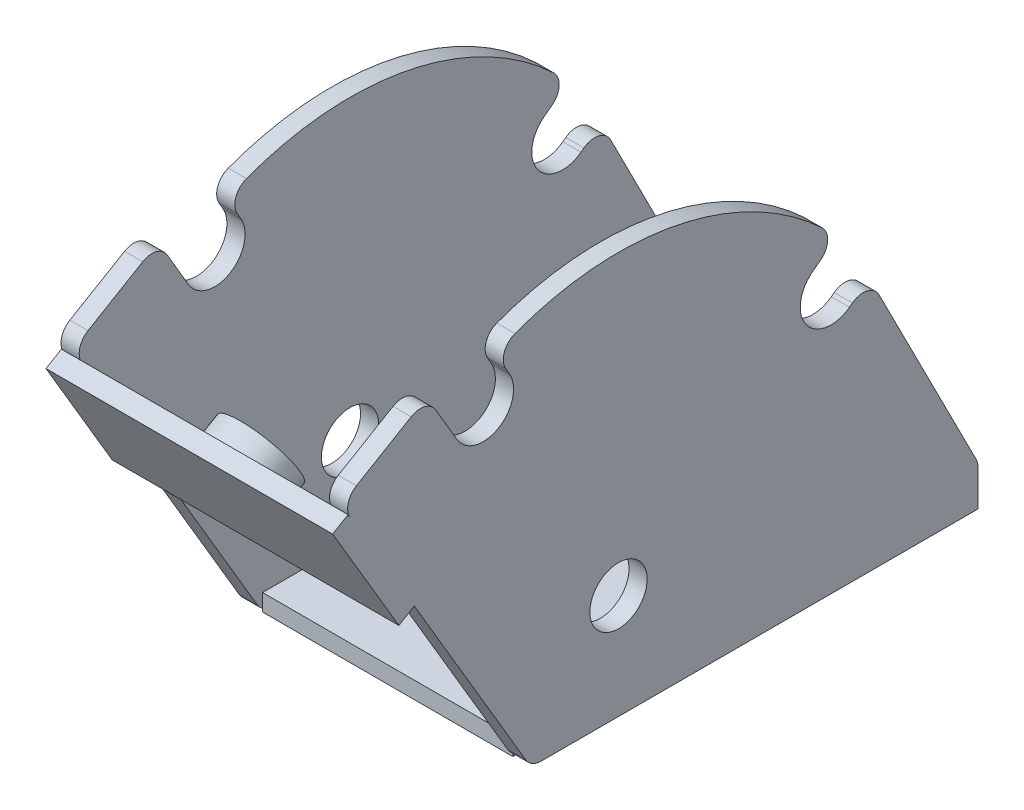
SolidWorks part; units mm, degrees
ref_plane "Front Plane" through (0, 0, 0) normal (0, 0, 1) x (1, 0, 0)
ref_plane "Top Plane" through (0, 0, 0) normal (0, 1, 0) x (1, 0, 0)
ref_plane "Right Plane" through (0, 0, 0) normal (1, 0, 0) x (0, 0, -1)
sketch "Sketch1" plane through (0, 0, 0) normal (0, 1, 0) x (1, 0, 0)
  line L0 (0, -1000) -> (0, 49000) construction
  line L1 (-17.78, -31.75) -> (17.78, -31.75)
  line L2 (-17.78, -31.75) -> (-17.78, 31.75)
  line L3 (-17.78, 31.75) -> (17.78, 31.75)
  line L4 (17.78, -31.75) -> (17.78, 31.75)
  line L5 (-17.78, -31.75) -> (17.78, 31.75) construction
  line L6 (-17.78, 31.75) -> (17.78, -31.75) construction
  circle A0 centre (-11.0109, 18.288) radius 3.0734
  circle A1 centre (-11.0109, -22.225) radius 3.0734
  circle A2 centre (11.0109, -22.225) radius 3.0734
  circle A3 centre (11.0109, 18.288) radius 3.0734
  point P0 (0, 0)
  dimension "D3" = 6.1468
  dimension "D1" = 35.56
  dimension "D2" = 63.5
  dimension "D4" = 9.525
  dimension "D5" = 6.7691
  dimension "D6" = 13.462
extrude "Boss-Extrude1" add sketch "Sketch1" along normal blind 2.4003
sketch "Sketch2" plane through (17.78, 0, 0) normal (1, 0, 0) x (0, 0, -1)
  line L0 (31.75, 0) -> (31.75, 5.1191)
  line L1 (31.75, 0) -> (-30.2995, 0)
  line L2 (-32.4871, 1.2492) -> (-57.4371, 43.5324)
  line L3 (-35.3361, 50.8042) -> (-34.8166, 49.9161)
  line L4 (31.4742, 6.2702) -> (17.6936, 33.377)
  line L5 (-45.2777, 50.696) -> (-42.271, 45.5558)
  line L6 (-56.5403, 47.0108) -> (-48.761, 51.6011)
  line L7 (-42.271, 45.5558) -> (-34.8166, 49.9161) construction
  line L8 (9.3783, 41.7831) -> (8.2564, 40.944)
  line L9 (13.908, 34.2599) -> (13.4898, 33.9471)
  line L10 (8.2564, 40.944) -> (13.4898, 33.9471) construction
  line L11 (-38.5438, 47.7359) -> (-19.3166, 14.8653) construction
  line L12 (-19.3166, 14.8653) -> (10.8731, 37.4455) construction
  arc A0 (-34.0281, 54.4677) -> (9.5952, 45.6691) centre (-19.3166, 14.8653) cw
  circle A1 centre (-19.3166, 14.8653) radius 4.0704
  arc A2 (-42.271, 45.5558) -> (-34.8166, 49.9161) centre (-38.5438, 47.7359) ccw
  arc A3 (8.2564, 40.944) -> (13.4898, 33.9471) centre (10.8731, 37.4455) ccw
  arc A4 (-30.2995, 0) -> (-32.4871, 1.2492) centre (-30.2995, 2.54) cw
  arc A5 (31.75, 5.1191) -> (31.4742, 6.2702) centre (29.21, 5.1191) ccw
  arc A6 (17.6936, 33.377) -> (13.908, 34.2599) centre (15.4294, 32.2259) ccw
  arc A7 (9.5952, 45.6691) -> (9.3783, 41.7831) centre (7.857, 43.8171) cw
  arc A8 (-35.3361, 50.8042) -> (-34.0281, 54.4677) centre (-33.1436, 52.0867) cw
  arc A9 (-45.2777, 50.696) -> (-48.761, 51.6011) centre (-47.4701, 49.4136) ccw
  arc A10 (-57.4371, 43.5324) -> (-56.5403, 47.0108) centre (-55.2495, 44.8232) cw
  point P20 (-31.75, 0)
  point P23 (31.75, 5.7277)
  point P26 (16.3255, 36.068)
  point P33 (-46.565, 52.8969)
  point P36 (-58.7279, 45.72)
  dimension "D2" = 8.1407
  dimension "D12" = 42.2465
  dimension "D15" = 2.54
  dimension "D1" = 14.8654
  dimension "D3" = 18.2626
  dimension "D4" = 53.086
  dimension "D5" = 45.72
  dimension "D6" = 14.1224
  dimension "D7" = 8.636
  dimension "D8" = 38.0809
  dimension "D9" = 34.036
  dimension "D10" = 5.7277
  dimension "D11" = 36.068
  dimension "D13" = 8.7376
  dimension "D14" = 37.6999
extrude "Boss-Extrude2" add sketch "Sketch2" along normal blind 2.5781
ref_plane "Plane1" through (0, 0, 0) normal (-1, 0, 0) x (0, 0, 1)
mirror "Mirror1" about plane through (0, 0, 0) normal (-1, 0, 0) of "Boss-Extrude2"
sketch "Sketch3" plane through (0, -13.8962, 23.5503) normal (0, -0.5082, 0.8612) x (1, 0, 0)
  line L0 (-20.3581, 66.6811) -> (-20.3581, 17.5855) construction
  line L1 (-20.3581, 48.7585) -> (20.3581, 48.7585)
  line L2 (-20.3581, 48.7585) -> (-20.3581, 67.2751)
  line L3 (-20.3581, 67.2751) -> (20.3581, 67.2751)
  line L4 (20.3581, 48.7585) -> (20.3581, 67.2751)
  line L5 (20.3581, 66.6811) -> (20.3581, 17.5855) construction
  line L6 (-17.78, 18.2023) -> (17.78, 18.2023) construction
  dimension "D1" = 18.5166
  dimension "D2" = 30.5562
extrude "Boss-Extrude3" add sketch "Sketch3" along normal blind 2.54
sketch "Sketch4" plane through (0, -13.8962, 23.5503) normal (0, 0.5082, -0.8612) x (-1, 0, 0)
  line L0 (-20.3581, 67.2751) -> (20.3581, 67.2751) construction
  line L1 (-20.3581, 48.7585) -> (-20.3581, 67.2751) construction
  circle A0 centre (0, 58.0168) radius 5.5626
  point P4 (0, 67.2751)
  point P7 (-20.3581, 58.0168)
  dimension "D1" = 11.1252
extrude "Boss-Extrude4" add sketch "Sketch4" along normal blind 3.7846
